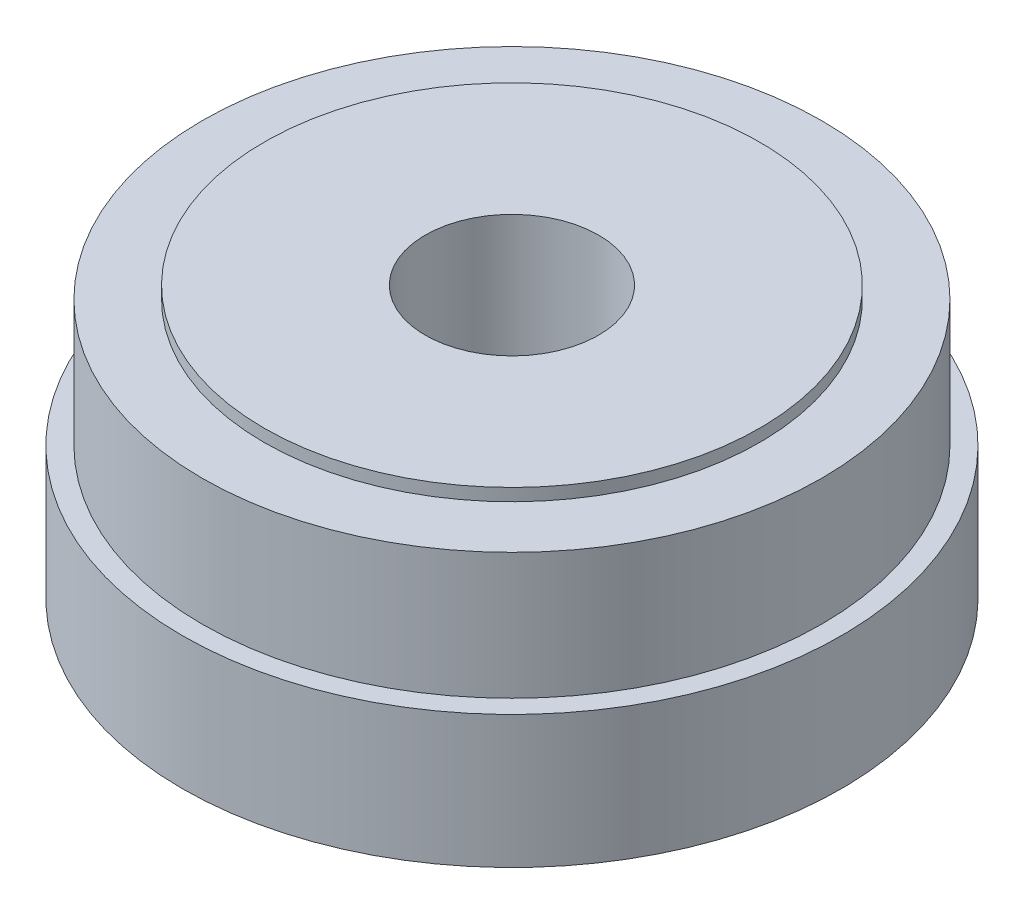
SolidWorks part; units mm, degrees
ref_plane "Front Plane" through (0, 0, 0) normal (0, 0, 1) x (1, 0, 0)
ref_plane "Top Plane" through (0, 0, 0) normal (0, 1, 0) x (1, 0, 0)
ref_plane "Right Plane" through (0, 0, 0) normal (1, 0, 0) x (0, 0, -1)
sketch "Sketch1" plane through (0, 0, 0) normal (0, 1, 0) x (1, 0, 0)
  circle A0 centre (0, 0) radius 133
extrude "Boss-Extrude1" add sketch "Sketch1" along normal blind 53.5
sketch "Sketch2" plane through (0, 53.5, 0) normal (0, 1, 0) x (1, 0, 0)
  circle A0 centre (0, 0) radius 125
extrude "Boss-Extrude2" add sketch "Sketch2" along normal blind 51
sketch "Sketch3" plane through (0, 104.5, 0) normal (0, 1, 0) x (1, 0, 0)
  circle A0 centre (0, 0) radius 100
extrude "Boss-Extrude3" add sketch "Sketch3" along normal blind 5
sketch "Sketch4" plane through (0, 0, 0) normal (0, -1, 0) x (1, 0, 0)
  circle A0 centre (0, 0) radius 106
extrude "Boss-Extrude4" add sketch "Sketch4" along normal blind 12
sketch "Sketch5" plane through (0, -12, 0) normal (0, -1, 0) x (1, 0, 0)
  circle A0 centre (0, 0) radius 60
  dimension "D1" = 120
extrude "Boss-Extrude5" add sketch "Sketch5" along normal blind 11
sketch "Sketch6" plane through (0, -23, 0) normal (0, -1, 0) x (1, 0, 0)
  circle A0 centre (0, 0) radius 35
extrude "Cut-Extrude1" cut sketch "Sketch6" against normal through all
